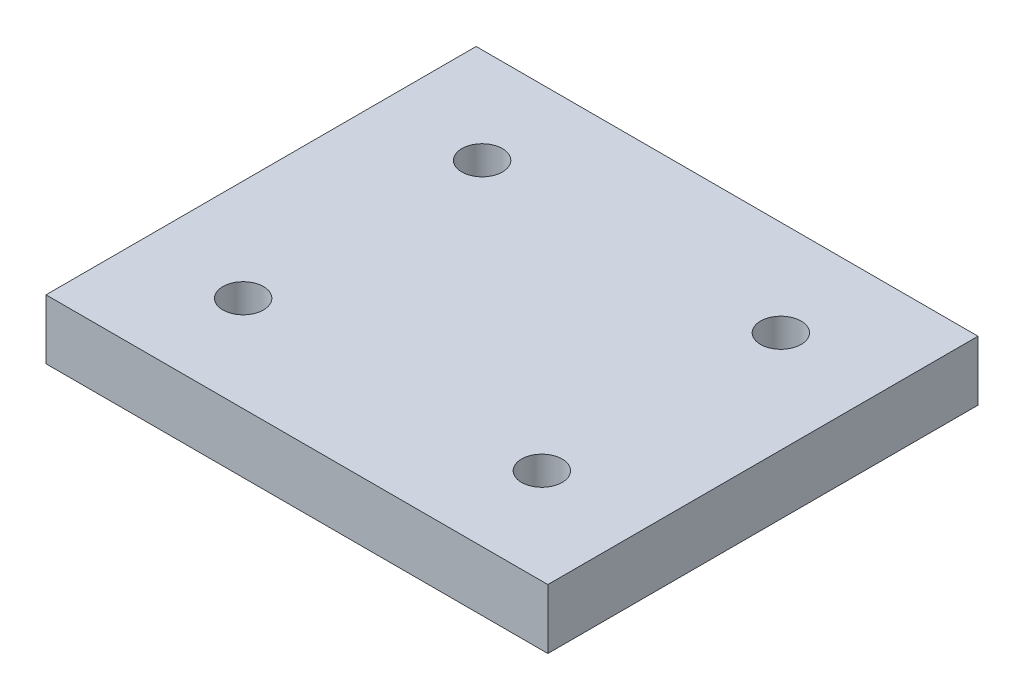
SolidWorks part; units mm, degrees
ref_plane "정면" through (0, 0, 0) normal (0, 0, 1) x (1, 0, 0)
ref_plane "윗면" through (0, 0, 0) normal (0, 1, 0) x (1, 0, 0)
ref_plane "우측면" through (0, 0, 0) normal (1, 0, 0) x (0, 0, -1)
sketch "스케치1" plane through (0, 0, 0) normal (0, 1, 0) x (1, 0, 0)
  line L1 (0, 0) -> (42, 0)
  line L2 (0, 0) -> (0, 36)
  line L3 (0, 36) -> (42, 36)
  line L4 (42, 0) -> (42, 36)
  dimension "D1" = 42
  dimension "D2" = 36
extrude "보스-돌출1" add sketch "스케치1" along normal blind 5
sketch "스케치2" plane through (0, 5, 0) normal (0, 1, 0) x (1, 0, 0)
  line L0 (33.5, 28) -> (42, 28) construction
  line L1 (8.5, 28) -> (33.5, 28) construction
  line L2 (8.5, 28) -> (8.5, 8) construction
  line L3 (8.5, 8) -> (33.5, 8) construction
  line L4 (33.5, 28) -> (33.5, 8) construction
  line L5 (42, 0) -> (42, 36) construction
  line L6 (8.5, 28) -> (0, 28) construction
  line L7 (0, 36) -> (0, 0) construction
  line L8 (8.5, 28) -> (8.5, 36) construction
  line L9 (42, 36) -> (0, 36) construction
  line L10 (8.5, 8) -> (8.5, 0) construction
  line L11 (0, 0) -> (42, 0) construction
  circle A0 centre (33.5, 28) radius 1.7
  circle A1 centre (33.5, 8) radius 1.7
  circle A2 centre (8.5, 8) radius 1.7
  circle A3 centre (8.5, 28) radius 1.7
  dimension "D3" = 3.4
  dimension "D1" = 25
  dimension "D2" = 20
  dimension "D4" = 8
  dimension "D5" = 8.5
extrude "컷-돌출1" cut sketch "스케치2" against normal blind 5
